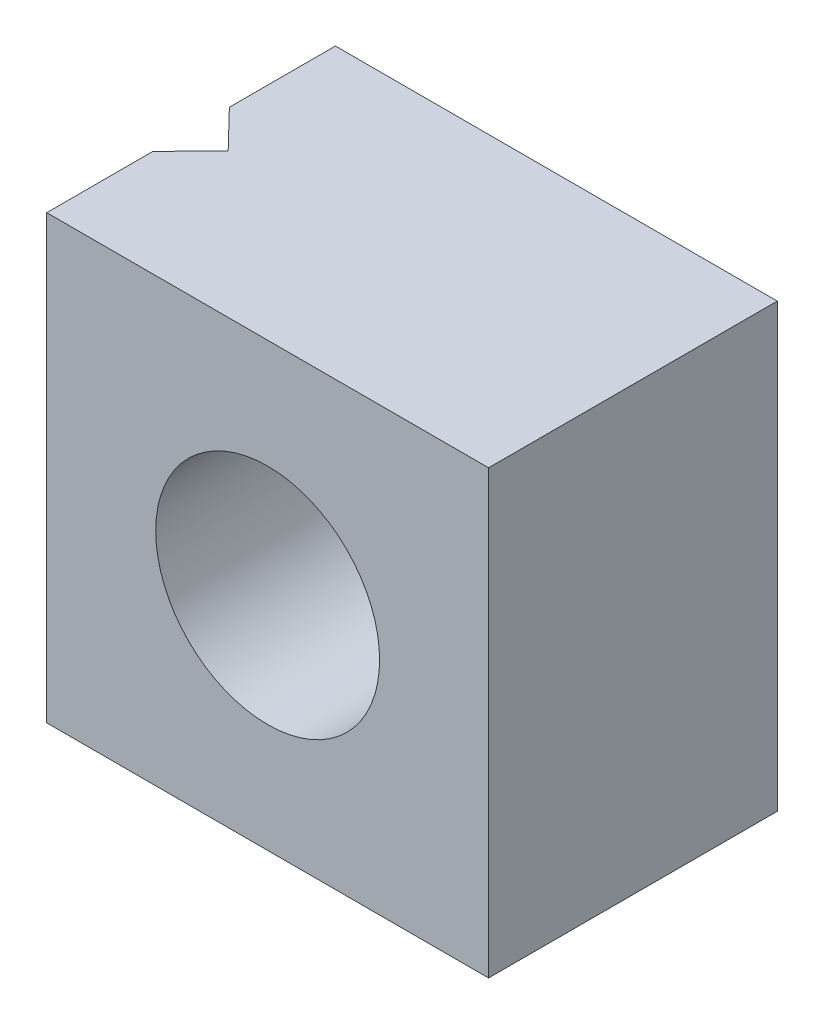
SolidWorks part; units mm, degrees
ref_plane "Front Plane" through (0, 0, 0) normal (0, 0, 1) x (1, 0, 0)
ref_plane "Top Plane" through (0, 0, 0) normal (0, 1, 0) x (1, 0, 0)
ref_plane "Right Plane" through (0, 0, 0) normal (1, 0, 0) x (0, 0, -1)
sketch "Sketch1" plane through (0, 0, 0) normal (0, 0, 1) x (1, 0, 0)
  line L0 (0, 0) -> (19.05, -19.05) construction
  line L1 (0, 0) -> (19.05, 0)
  line L2 (0, 0) -> (0, -19.05)
  line L3 (0, -19.05) -> (19.05, -19.05)
  line L4 (19.05, 0) -> (19.05, -19.05)
  circle A0 centre (9.525, -9.525) radius 4.826
  dimension "D3" = 9.652
  dimension "D1" = 19.05
  dimension "D2" = 19.05
extrude "Boss-Extrude1" add sketch "Sketch1" against normal blind 12.446
sketch "Sketch2" plane through (0, 0, 0) normal (0, 1, 0) x (1, 0, 0)
  line L0 (0, 0) -> (0, 12.446) construction
  line L1 (19.05, 6.223) -> (0, 6.223) construction
  line L2 (19.05, 12.446) -> (19.05, 0) construction
  line L3 (0, 4.572) -> (1.6002, 6.223)
  line L4 (1.6002, 6.223) -> (0, 7.874)
  dimension "D1" = 4.572
  dimension "D2" = 4.572
  dimension "D3" = 1.6002
extrude "Cut-Extrude1" cut sketch "Sketch2" against normal through all and the other way through all
